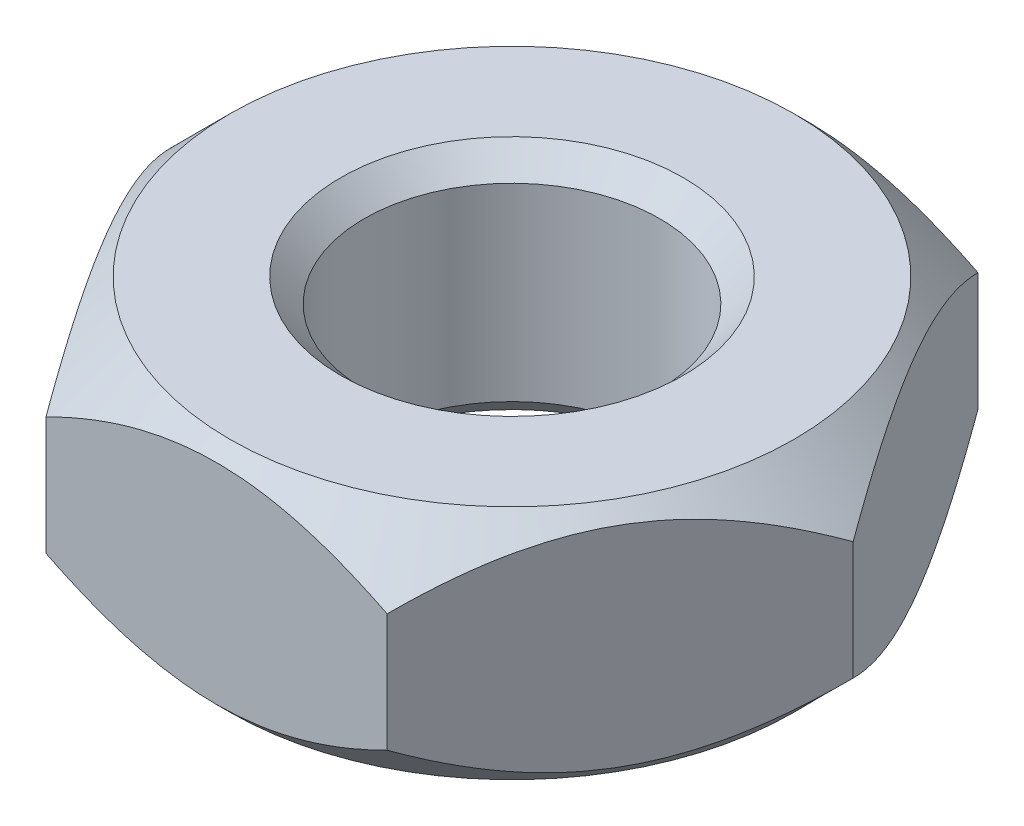
SolidWorks part; units mm, degrees
ref_plane "Спереди" through (0, 0, 0) normal (0, 0, 1) x (1, 0, 0)
ref_plane "Сверху" through (0, 0, 0) normal (0, 1, 0) x (1, 0, 0)
ref_plane "Справа" through (0, 0, 0) normal (1, 0, 0) x (0, 0, -1)
sketch "Эскиз1" plane through (0, 0, 0) normal (0, 1, 0) x (1, 0, 0)
  line L0 (-1.4434, 2.5) -> (1.4434, 2.5)
  line L1 (1.4434, 2.5) -> (2.8868, 0)
  line L2 (2.8868, 0) -> (1.4434, -2.5)
  line L3 (1.4434, -2.5) -> (-1.4434, -2.5)
  line L4 (-1.4434, -2.5) -> (-2.8868, 0)
  line L5 (-2.8868, 0) -> (-1.4434, 2.5)
  dimension "D5" = 2.5
  dimension "D2" = 120
  dimension "D3" = 120
  dimension "D4" = 120
  dimension "D6" = 2.5
  dimension "D7" = 2.5
  dimension "D8" = 2.5
  dimension "D9" = 2.5
  dimension "D10" = 120
  dimension "D11" = 2.5
extrude "Вытянуть1" add sketch "Эскиз1" against normal blind 2
sketch "Эскиз5" plane through (0, -2, 0) normal (0, -1, 0) x (1, 0, 0)
  circle A0 centre (0, 0) radius 1.25
  dimension "D1" = 2.5
extrude "Вырез-Вытянуть1" cut sketch "Эскиз5" against normal through all
ref_axis "Ось1" through (0, 0, 0) along (0, -1, 0)
ref_plane "Плоскость1" through (0, 0, 0) normal (0, 0, 1) x (1, 0, 0)
sketch "Эскиз4" plane through (0, 0, 0) normal (0, 0, 1) x (1, 0, 0)
  line L0 (-2.8868, -0.5) -> (-2.3868, 0)
  line L1 (-2.8868, -2) -> (-2.8868, 0) construction
  line L2 (-2.8868, 0) -> (-1.4434, 0) construction
  line L3 (-2.3868, 0) -> (-2.8868, 0)
  line L4 (-2.8868, 0) -> (-2.8868, -0.5)
  line L5 (-2.8868, -1.5) -> (-2.3868, -2)
  line L6 (-2.8868, -2) -> (-1.4434, -2) construction
  line L7 (-2.3868, -2) -> (-2.8868, -2)
  line L8 (-2.8868, -2) -> (-2.8868, -1.5)
  dimension "D1" = 0.5
  dimension "D2" = 0.5
  dimension "D3" = 0.5
  dimension "D4" = 0.5
revolve "Вырез-Повернуть1" cut sketch "Эскиз4" angle 360 about axis through (0, 0, 0) along (0, -1, 0)
chamfer "Фаска1" distance 0.2 angle 45 2 edges at (0, -2, -1.25) (0, 0, -1.25)
